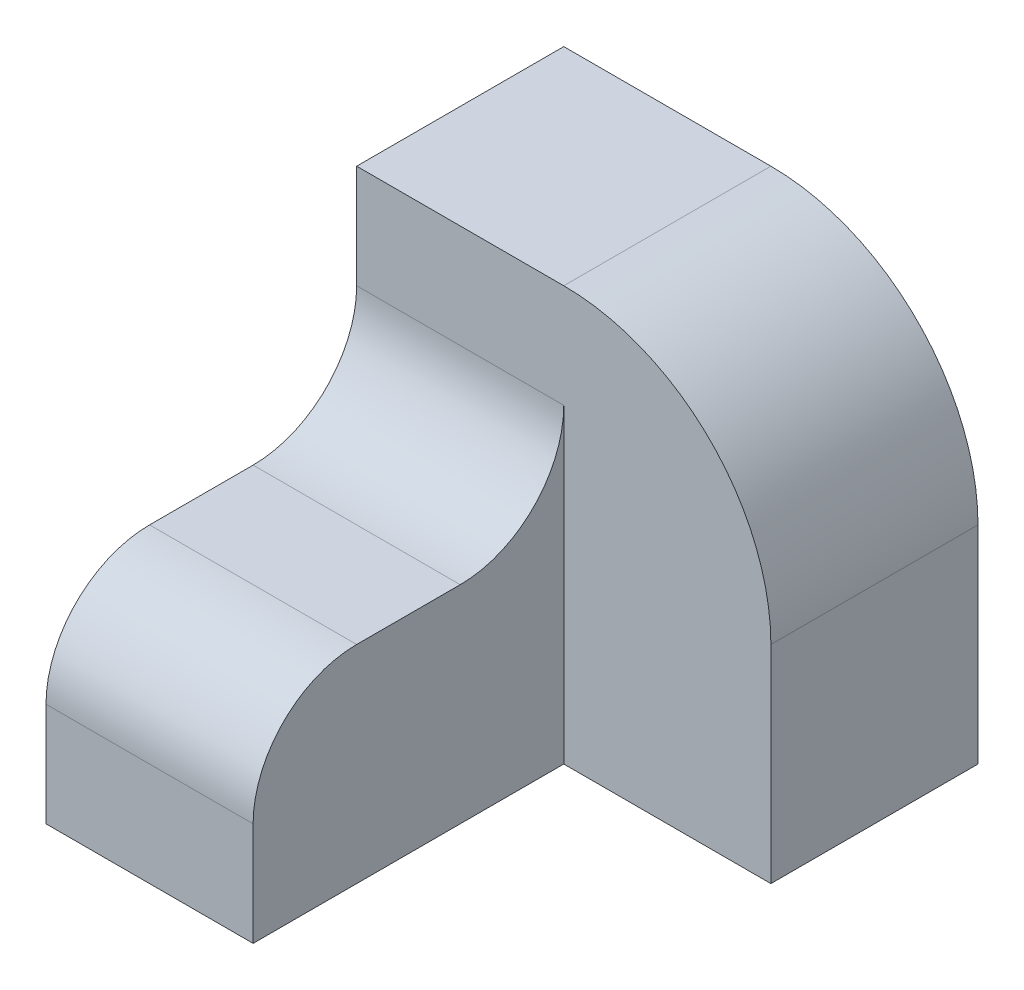
SolidWorks part; units mm, degrees
ref_plane "前基準面" through (0, 0, 0) normal (0, 0, 1) x (1, 0, 0)
ref_plane "上基準面" through (0, 0, 0) normal (0, 1, 0) x (1, 0, 0)
ref_plane "右基準面" through (0, 0, 0) normal (1, 0, 0) x (0, 0, -1)
sketch "草圖1" plane through (0, 0, 0) normal (0, 1, 0) x (1, 0, 0)
  line L1 (0, 0) -> (20, 0)
  line L2 (0, 0) -> (0, 10)
  line L3 (0, 10) -> (20, 10)
  line L4 (20, 0) -> (20, 10)
  dimension "D1" = 20
  dimension "D2" = 10
extrude "填料-伸長1" add sketch "草圖1" along normal blind 20
sketch "草圖2" plane through (0, 0, 0) normal (0, 0, 1) x (1, 0, 0)
  line L1 (0, 0) -> (10, 0)
  line L2 (0, 0) -> (0, 10)
  line L3 (0, 10) -> (10, 10)
  line L4 (10, 0) -> (10, 10)
  dimension "D1" = 10
  dimension "D2" = 10
extrude "填料-伸長2" add sketch "草圖2" along normal blind 15
fillet "圓角1" radius 5 2 edges at (5, 10, 15) (5, 10, 0)
fillet "圓角2" radius 10 1 edges at (20, 20, -5)
